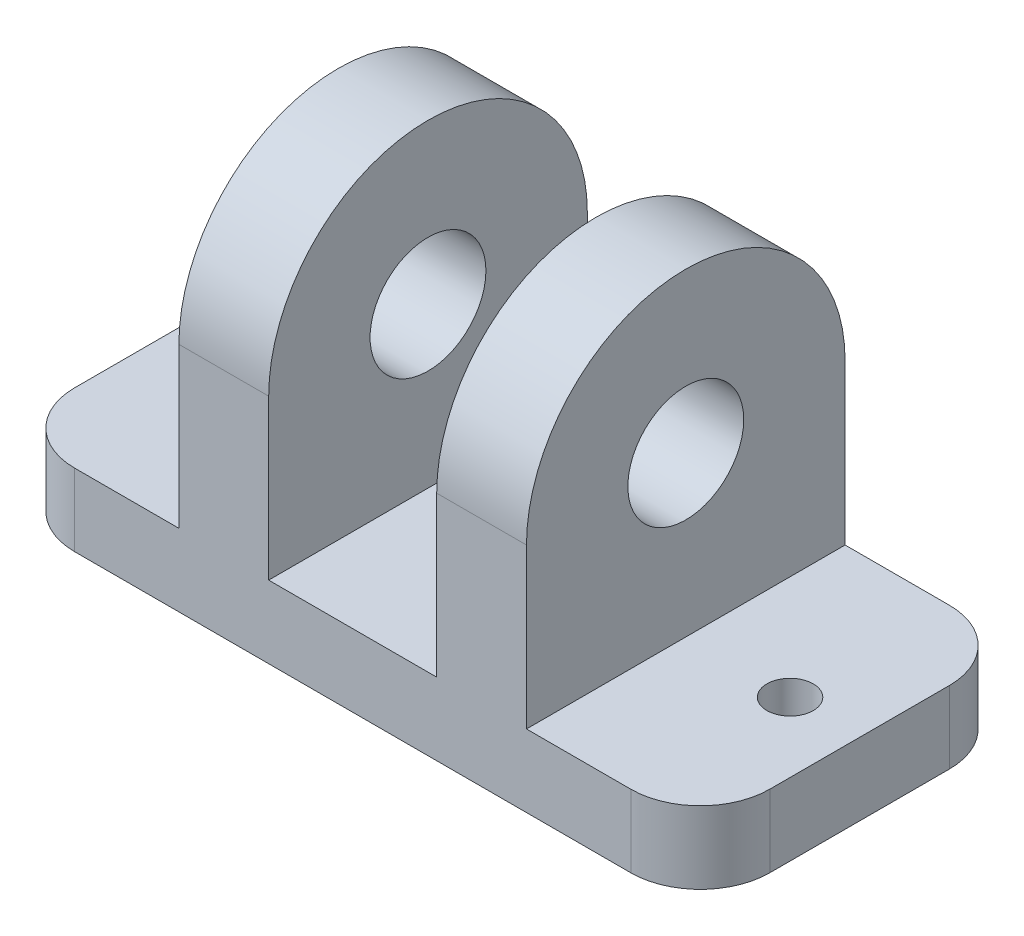
SolidWorks part; units mm, degrees
ref_plane "Front Plane" through (0, 0, 0) normal (0, 0, 1) x (1, 0, 0)
ref_plane "Top Plane" through (0, 0, 0) normal (0, 1, 0) x (1, 0, 0)
ref_plane "Right Plane" through (0, 0, 0) normal (1, 0, 0) x (0, 0, -1)
sketch "Sketch1" plane through (0, 0, 0) normal (0, 1, 0) x (1, 0, 0)
  line L1 (-60, -27.5) -> (60, -27.5)
  line L2 (-60, -27.5) -> (-60, 27.5)
  line L3 (-60, 27.5) -> (60, 27.5)
  line L4 (60, -27.5) -> (60, 27.5)
  line L5 (-60, -27.5) -> (60, 27.5) construction
  line L6 (-60, 27.5) -> (60, -27.5) construction
  point P0 (0, 0)
  dimension "D1" = 120
  dimension "D2" = 55
extrude "Boss-Extrude1" add sketch "Sketch1" against normal blind 12.5
sketch "Sketch3" plane through (0, 0, 0) normal (0, 1, 0) x (1, 0, 0)
  line L0 (60, 27.5) -> (-60, 27.5) construction
  line L1 (14.5, 27.5) -> (30, 27.5)
  line L2 (14.5, 27.5) -> (14.5, -27.5)
  line L3 (14.5, -27.5) -> (30, -27.5)
  line L4 (30, 27.5) -> (30, -27.5)
  line L5 (-60, -27.5) -> (60, -27.5) construction
  line L7 (-30, 27.5) -> (-14.5, 27.5)
  line L8 (-30, 27.5) -> (-30, -27.5)
  line L9 (-30, -27.5) -> (-14.5, -27.5)
  line L10 (-14.5, 27.5) -> (-14.5, -27.5)
  dimension "D1" = 15.5
  dimension "D2" = 15.5
  dimension "D3" = 30
  dimension "D4" = 30
extrude "Boss-Extrude2" add sketch "Sketch3" along normal blind 55
sketch "Sketch6" plane through (30, 0, 0) normal (1, 0, 0) x (0, 0, -1)
  line L0 (27.5, 55) -> (27.5, 0) construction
  line L1 (-27.5, 55) -> (-27.5, 0) construction
  line L2 (-27.5, 55) -> (27.5, 55) construction
  line L3 (-27.5, 0) -> (27.5, 0) construction
  line L4 (-27.5, 27.5) -> (-27.5, 55)
  line L5 (-27.5, 55) -> (27.5, 55)
  line L6 (27.5, 55) -> (27.5, 27.5)
  arc A0 (27.5, 27.5) -> (-27.5, 27.5) centre (0, 27.5) ccw
  circle A1 centre (0, 27.5) radius 10
  line M4 (27.5, 0) -> (27.5, 55)
  line M5 (27.5, 55) -> (-27.5, 55)
  line M6 (-27.5, 55) -> (-27.5, 0)
  dimension "D1" = 20
extrude "Cut-Extrude1" cut sketch "Sketch6" against normal through all contours A0 L5 M6 | A0 M4 M5 | A1
sketch "Sketch7" plane through (0, 0, 0) normal (0, 1, 0) x (1, 0, 0)
  line L1 (60, 15.5) -> (60, -15.5)
  line L2 (60, -27.5) -> (60, 27.5) construction
  line L4 (-60, -15.5) -> (-60, 15.5)
  line L5 (-48, 27.5) -> (-60, 27.5)
  line L6 (-60, 27.5) -> (-60, 15.5)
  line L7 (-60, -15.5) -> (-60, -27.5)
  line L8 (-60, -27.5) -> (-48, -27.5)
  line L9 (48, -27.5) -> (60, -27.5)
  line L10 (60, -27.5) -> (60, -15.5)
  line L11 (60, 15.5) -> (60, 27.5)
  line L12 (60, 27.5) -> (48, 27.5)
  arc A0 (48, 27.5) -> (60, 15.5) centre (48, 15.5) cw
  arc A1 (60, -15.5) -> (48, -27.5) centre (48, -15.5) cw
  arc A2 (-48, -27.5) -> (-60, -15.5) centre (-48, -15.5) cw
  arc A3 (-60, 15.5) -> (-48, 27.5) centre (-48, 15.5) cw
  point P11 (60, 27.5)
  point P14 (60, -27.5)
  point P17 (-60, -27.5)
  point P20 (-60, 27.5)
  dimension "D1" = 12
extrude "Cut-Extrude4" cut sketch "Sketch7" against normal through all contours A1 A3 A0 | L2 A2 A1 | L10 A1 L9 | L12 A0 L11
sketch "Sketch8" plane through (0, 0, 0) normal (0, 1, 0) x (1, 0, 0)
  line L2 (-60, 15.5) -> (-60, -15.5) construction
  line L4 (60, -15.5) -> (60, 15.5) construction
  circle A0 centre (-48, 0) radius 4
  circle A1 centre (48, 0) radius 4
  dimension "D1" = 12
  dimension "D3" = 8
  dimension "D4" = 8
  dimension "D2" = 12
extrude "Cut-Extrude5" cut sketch "Sketch8" against normal through all
